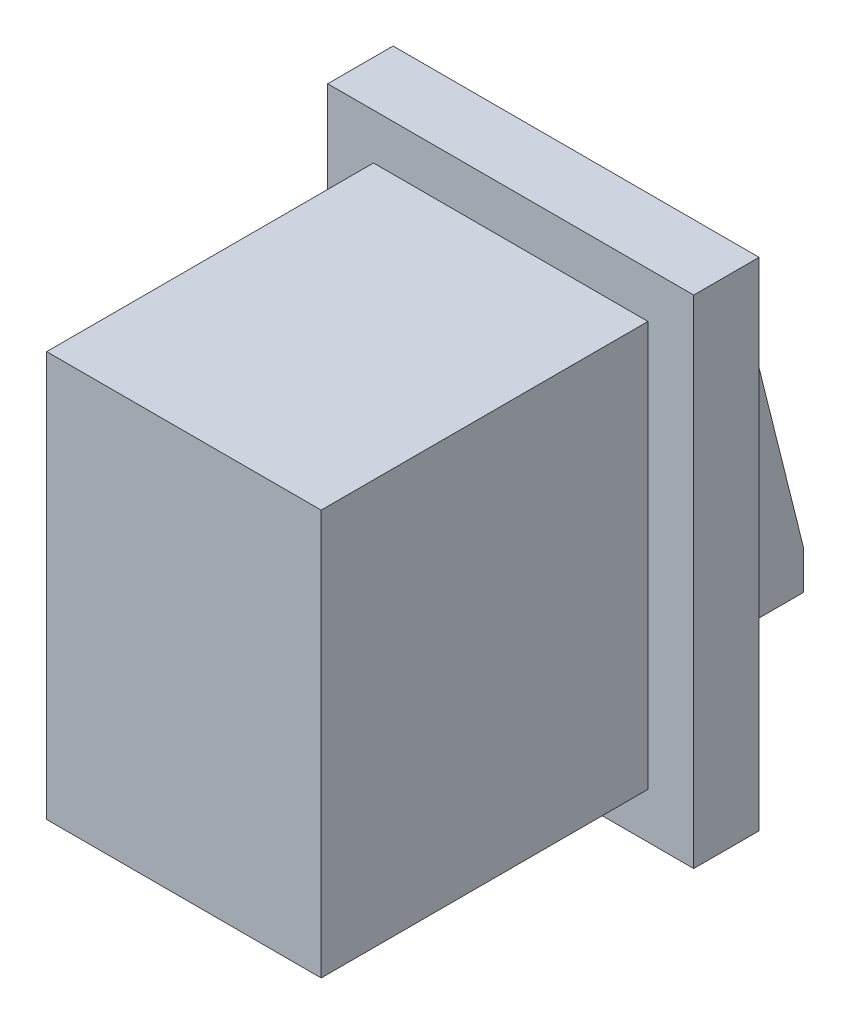
SolidWorks part; units mm, degrees
ref_plane "Front Plane" through (0, 0, 0) normal (0, 0, 1) x (1, 0, 0)
ref_plane "Top Plane" through (0, 0, 0) normal (0, 1, 0) x (1, 0, 0)
ref_plane "Right Plane" through (0, 0, 0) normal (1, 0, 0) x (0, 0, -1)
sketch "Sketch1" plane through (0, 0, 0) normal (0, 0, 1) x (1, 0, 0)
  line L1 (-10.5, -15.5) -> (10.5, -15.5)
  line L2 (-10.5, -15.5) -> (-10.5, 15.5)
  line L3 (-10.5, 15.5) -> (10.5, 15.5)
  line L4 (10.5, -15.5) -> (10.5, 15.5)
  line L5 (-10.5, -15.5) -> (10.5, 15.5) construction
  line L6 (-10.5, 15.5) -> (10.5, -15.5) construction
  point P0 (0, 0)
  dimension "D1" = 31
  dimension "D2" = 21
extrude "Boss-Extrude1" add sketch "Sketch1" along normal blind 25
sketch "Sketch2" plane through (0, 0, 0) normal (0, 0, -1) x (-1, 0, 0)
  line L1 (-14, -19) -> (14, -19)
  line L2 (-14, -19) -> (-14, 19)
  line L3 (-14, 19) -> (14, 19)
  line L4 (14, -19) -> (14, 19)
  line L5 (-14, -19) -> (14, 19) construction
  line L6 (-14, 19) -> (14, -19) construction
  point P0 (0, 0)
  dimension "D1" = 28
  dimension "D2" = 38
extrude "Boss-Extrude2" add sketch "Sketch2" along normal blind 5
sketch "Sketch3" plane through (0, 0, -5) normal (0, 0, -1) x (-1, 0, 0)
  line L1 (-7.3843, -11.5191) -> (7.3843, -11.5191)
  line L2 (-7.3843, -11.5191) -> (-7.3843, 11.5191)
  line L3 (-7.3843, 11.5191) -> (7.3843, 11.5191)
  line L4 (7.3843, -11.5191) -> (7.3843, 11.5191)
  line L5 (-7.3843, -11.5191) -> (7.3843, 11.5191) construction
  line L6 (-7.3843, 11.5191) -> (7.3843, -11.5191) construction
  point P0 (0, 0)
extrude "Boss-Extrude3" add sketch "Sketch3" along normal blind 10
chamfer "Chamfer1" distance 5 distance2 20 1 edges at (0, 11.5191, -15)
